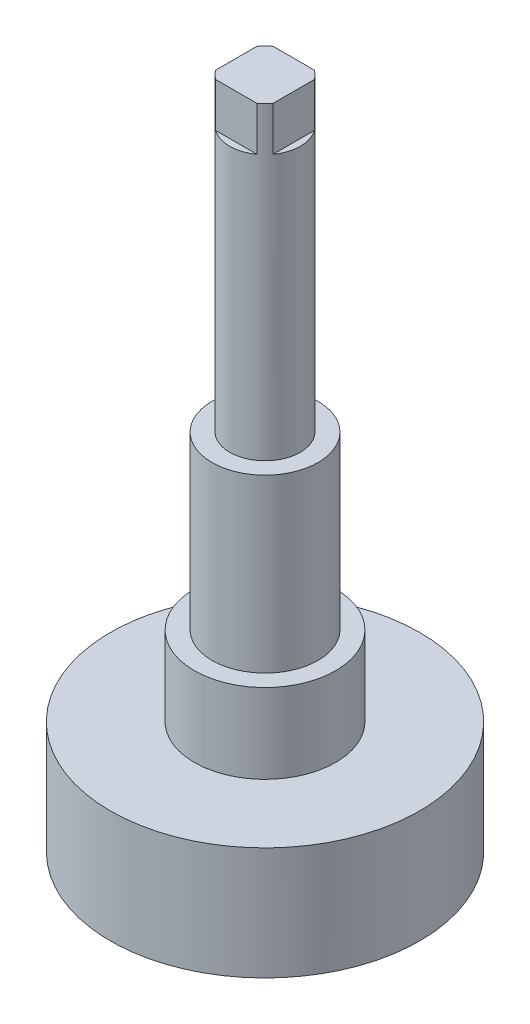
SolidWorks part; units mm, degrees
material "Plain Carbon Steel"
ref_plane "Front Plane" through (0, 0, 0) normal (0, 0, 1) x (1, 0, 0)
ref_plane "Top Plane" through (0, 0, 0) normal (0, 1, 0) x (1, 0, 0)
ref_plane "Right Plane" through (0, 0, 0) normal (1, 0, 0) x (0, 0, -1)
sketch "Sketch1" plane through (0, 0, 0) normal (0, 1, 0) x (1, 0, 0)
  circle A0 centre (0, 0) radius 5
  dimension "D1" = 10
extrude "Boss-Extrude1" add sketch "Sketch1" against normal blind 8
sketch "Sketch2" plane through (0, 0, 0) normal (0, 1, 0) x (1, 0, 0)
  circle A0 centre (0, 0) radius 17.5
  dimension "D1" = 35
extrude "Boss-Extrude2" add sketch "Sketch2" along normal blind 5
sketch "Sketch3" plane through (0, 0, 0) normal (0, -1, 0) x (1, 0, 0)
  circle A0 centre (0, 0) radius 17.5
  circle A1 centre (0, 0) radius 13.5
  dimension "D1" = 35
  dimension "D2" = 27
extrude "Boss-Extrude3" add sketch "Sketch3" along normal blind 7.75
sketch "Sketch4" plane through (0, 5, 0) normal (0, 1, 0) x (1, 0, 0)
  circle A0 centre (0, 0) radius 6
extrude "Boss-Extrude4" add sketch "Sketch4" along normal blind 58.4
sketch "Sketch7" plane through (0, 63.4, 0) normal (0, 1, 0) x (1, 0, 0)
  circle A0 centre (0, 0) radius 4
  circle A1 centre (0, 0) radius 7.9981
extrude "Cut-Extrude1" cut sketch "Sketch7" against normal blind 30
sketch "Sketch6" plane through (0, 63.4, 0) normal (0, 1, 0) x (1, 0, 0)
  line L1 (-2.75, 2.75) -> (2.75, 2.75)
  line L2 (-2.75, 2.75) -> (-2.75, -2.75)
  line L3 (-2.75, -2.75) -> (2.75, -2.75)
  line L4 (2.75, 2.75) -> (2.75, -2.75)
  line L5 (0, -2.75) -> (0, 2.75) construction
  line L6 (-2.75, 0) -> (2.75, 0) construction
  point P0 (0, 0)
  dimension "D1" = 5.5
extrude "Boss-Extrude5" [suppressed] add sketch "Sketch6" along normal blind 5
sketch "Sketch8" plane through (0, 5, 0) normal (0, 1, 0) x (1, 0, 0)
  circle A0 centre (0, 0) radius 6
  circle A1 centre (0, 0) radius 8
extrude "Boss-Extrude6" add sketch "Sketch8" along normal blind 9
sketch "Sketch9" [suppressed] plane through (0, 63.4, 0) normal (0, 1, 0) x (1, 0, 0)
  line L0 (-44.2539, 0) -> (44.2539, 0) construction
  circle A0 centre (0, 0) radius 1.5
extrude "Cut-Extrude2" [suppressed] cut sketch "Sketch9" against normal blind 10
sketch "Sketch10" plane through (0, 63.4, 0) normal (0, 1, 0) x (1, 0, 0)
  line L0 (-3.25, 2.3318) -> (-3.25, -2.3318)
  line L3 (-2.3318, -3.25) -> (2.3318, -3.25)
  line L6 (3.25, -2.3318) -> (3.25, 2.3318)
  line L9 (2.3318, 3.25) -> (-2.3318, 3.25)
  circle A0 centre (0, 0) radius 4 construction
  circle A1 centre (0, 0) radius 4 construction
  arc A6 (-3.25, -2.3318) -> (-2.3318, -3.25) centre (0, 0) ccw
  arc A7 (-2.3318, 3.25) -> (-3.25, 2.3318) centre (0, 0) ccw
  arc A8 (3.25, 2.3318) -> (2.3318, 3.25) centre (0, 0) ccw
  arc A9 (2.3318, -3.25) -> (3.25, -2.3318) centre (0, 0) ccw
  dimension "D1" = 3.25
  dimension "D2" = 3.25
extrude "Boss-Extrude7" add sketch "Sketch10" along normal blind 5
